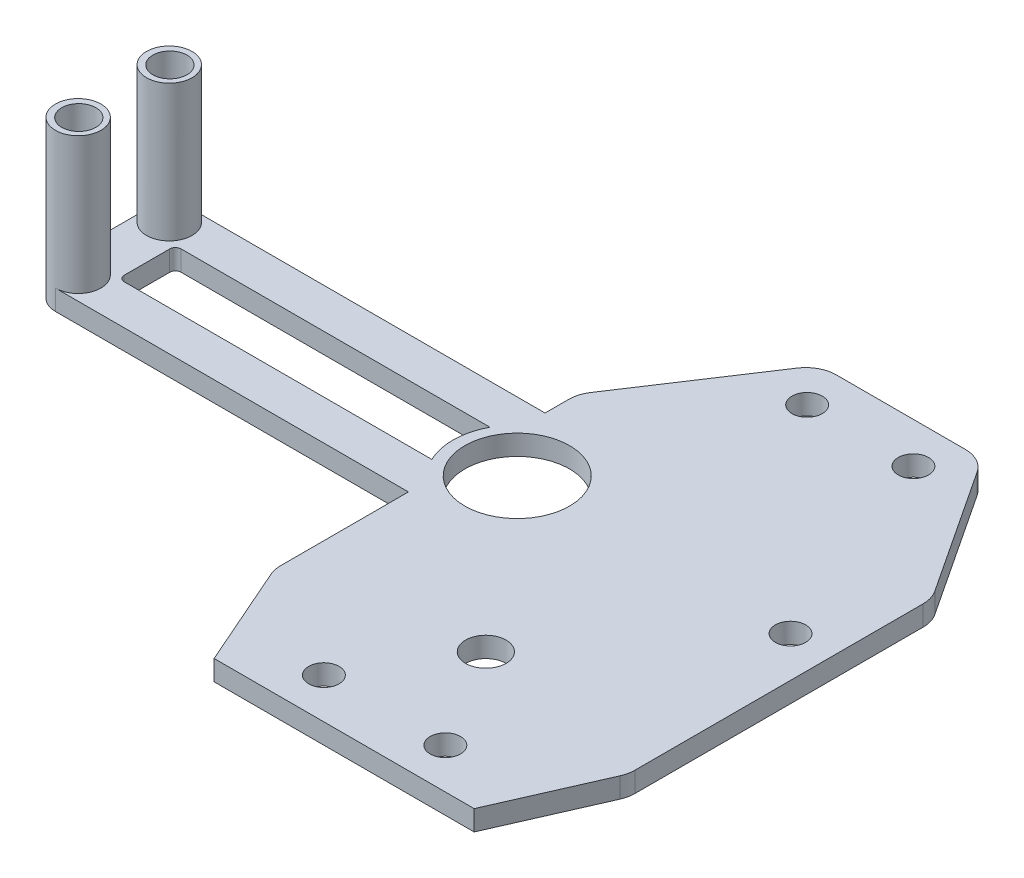
SolidWorks part; units mm, degrees
ref_plane "Alzado" through (0, 0, 0) normal (0, 0, 1) x (1, 0, 0)
ref_plane "Planta" through (0, 0, 0) normal (0, 1, 0) x (1, 0, 0)
ref_plane "Vista lateral" through (0, 0, 0) normal (1, 0, 0) x (0, 0, -1)
sketch "Croquis1" plane through (0, 0, 0) normal (0, 1, 0) x (1, 0, 0)
  line L0 (0, 0) -> (0, 62) construction
  line L2 (12.8466, 7) -> (17.5, 17.5997)
  line L3 (17.5, 17.5997) -> (17.5, 47.5997)
  line L4 (17.5, 47.5997) -> (8, 62)
  line L5 (8, 62) -> (-8, 62)
  line L6 (-12.8466, 7) -> (-17.5, 17.5997)
  line L7 (-17.5, 17.5997) -> (-17.5, 47.5997)
  line L8 (-17.5, 47.5997) -> (-8, 62)
  line L9 (-12.8466, 7) -> (12.8466, 7)
  line L10 (6.97, 22.2225) -> (17.5, 17.5997) construction
  line L11 (-5.25, 57.9943) -> (5.25, 57.9943) construction
  line L12 (-13.5, 37.5997) -> (13.5, 37.5997) construction
  line L16 (0, 39.0997) -> (0, 36.0997) construction
  line L17 (-6, 11) -> (6, 11) construction
  circle A0 centre (0, 21) radius 2
  circle A1 centre (-5.25, 57.9943) radius 1.5
  circle A2 centre (-13.5, 37.5997) radius 1.5
  circle A3 centre (13.5, 37.5997) radius 1.5
  circle A4 centre (5.25, 57.9943) radius 1.5
  circle A13 centre (-6, 11) radius 1.5
  circle A14 centre (6, 11) radius 1.5
  point P3 (0, 7)
  point P23 (0, 57.9943)
  point P24 (0, 37.5997)
  point P42 (0, 11)
  dimension "D7" = 4
  dimension "D8" = 4
  dimension "D9" = 10
  dimension "D10" = 3
  dimension "D20" = 12
  dimension "D1" = 62
  dimension "D2" = 35
  dimension "D3" = 7
  dimension "D4" = 16
  dimension "D5" = 30
  dimension "D11" = 10.5
  dimension "D12" = 27
  dimension "D13" = 22
  dimension "D14" = 10
extrude "Saliente-Extruir1" add sketch "Croquis1" along normal mid plane 2
fillet "Redondeo1" radius 3 6 edges at (-8, 0, -62) (8, 0, -62) (17.5, 0, -47.5997) (17.5, 0, -17.5997) (-17.5, 0, -17.5997) (-17.5, 0, -47.5997)
scale "Scale1" scale about centroid uniform scaling yes scale factor 0.888889
sketch "Sketch1" plane through (0, -0.8889, 0) normal (0, -1, 0) x (1, 0, 0)
  line L0 (-12, -37.1351) -> (-46.5, -37.1351) construction
  line L1 (-46.5, -33.1351) -> (-46.5, -41.1351) construction
  line L2 (-46.5, -41.1351) -> (-15.5556, -41.1351) construction
  line L3 (-15.5556, -45.2236) -> (-15.5556, -19.9169) construction
  line L4 (-46.5, -33.1351) -> (-15.5556, -33.1351) construction
  line L5 (-15.5556, -31.1351) -> (-46.5556, -31.1351)
  line L6 (-48.5556, -33.1351) -> (-48.5556, -41.1351)
  line L7 (-46.5556, -43.1351) -> (-15.5556, -43.1351)
  line L8 (-15.5556, -43.1351) -> (-15.5556, -39.6351)
  line L9 (-15.5556, -39.6351) -> (-44.0139, -39.6351)
  line L10 (-44.5139, -39.1351) -> (-44.5139, -35.1351)
  line L11 (-44.0139, -34.6351) -> (-15.5556, -34.6351)
  line L12 (-15.5556, -34.6351) -> (-15.5556, -31.1351)
  circle A0 centre (-46.5, -33.1351) radius 1.5
  circle A1 centre (-46.5, -41.1351) radius 1.5
  arc A2 (-48.5556, -41.1351) -> (-46.5556, -43.1351) centre (-46.5556, -41.1351) ccw
  arc A3 (-46.5556, -31.1351) -> (-48.5556, -33.1351) centre (-46.5556, -33.1351) ccw
  arc A4 (-44.0139, -39.6351) -> (-44.5139, -39.1351) centre (-44.0139, -39.1351) cw
  arc A5 (-44.5139, -35.1351) -> (-44.0139, -34.6351) centre (-44.0139, -35.1351) cw
  point P13 (0, 0)
  point P21 (-50.1003, -30.4014)
  point P22 (-50.4964, -44.7896)
  point P23 (0, 0)
  point P24 (0, 0)
  point P27 (-48.5556, -43.1351)
  point P30 (-48.5556, -31.1351)
  point P33 (-44.5139, -39.6351)
  point P36 (-44.5139, -34.6351)
  dimension "D3" = 3
  dimension "D6" = 2
  dimension "D7" = 0.5
  dimension "D1" = 34.5
  dimension "D2" = 8
  dimension "D4" = 12
  dimension "D5" = 31
  dimension "D8" = 5
extrude "Boss-Extrude1" add sketch "Sketch1" against normal up to surface (1.7778 mm away) up to face at (-5.3333, 0.8889, -12.1576)
sketch "Sketch2" plane through (0, 0.8889, 0) normal (0, 1, 0) x (1, 0, 0)
  line L0 (-16.899, 39.6351) -> (-15.5556, 39.6351)
  line L1 (-15.5556, 39.6351) -> (-44.0139, 39.6351) construction
  line L2 (-15.5556, 39.6351) -> (-15.5556, 34.6351)
  line L3 (-15.5556, 34.6351) -> (-17.0004, 34.6351)
  line L4 (-44.0139, 34.6351) -> (-15.5556, 34.6351) construction
  arc A1 (-16.899, 39.6351) -> (-17.0004, 34.6351) centre (-12, 37.0348) ccw
extrude "Boss-Extrude2" add sketch "Sketch2" against normal up to surface (1.7778 mm away) up to face at (-11.1081, -0.8889, -36.877)
sketch "Sketch3" plane through (0, 0.8889, 0) normal (0, 1, 0) x (1, 0, 0)
  circle A0 centre (-12, 37.1351) radius 4.6
  dimension "D1" = 9.2
extrude "Cut-Extrude1" cut sketch "Sketch3" against normal blind 10
sketch "Sketch4" plane through (0, 0.8889, 0) normal (0, 1, 0) x (1, 0, 0)
  arc A0 (-46.5556, 43.1351) -> (-48.5556, 41.1351) centre (-46.5556, 41.1351) ccw construction
  circle A1 centre (-46.5556, 41.1351) radius 2
  arc A2 (-48.5556, 33.1351) -> (-46.5556, 31.1351) centre (-46.5556, 33.1351) ccw construction
  circle A3 centre (-46.5556, 33.1351) radius 2
  circle A4 centre (-46.5, 41.1351) radius 1.5 construction
  circle A5 centre (-46.5, 41.1351) radius 1.5
  circle A6 centre (-46.5, 33.1351) radius 1.5 construction
  circle A7 centre (-46.5, 33.1351) radius 1.5
  point P6 (-46.5, 43.1351)
  point P8 (-46.2918, 31.1351)
extrude "Boss-Extrude3" add sketch "Sketch4" along normal blind 12
